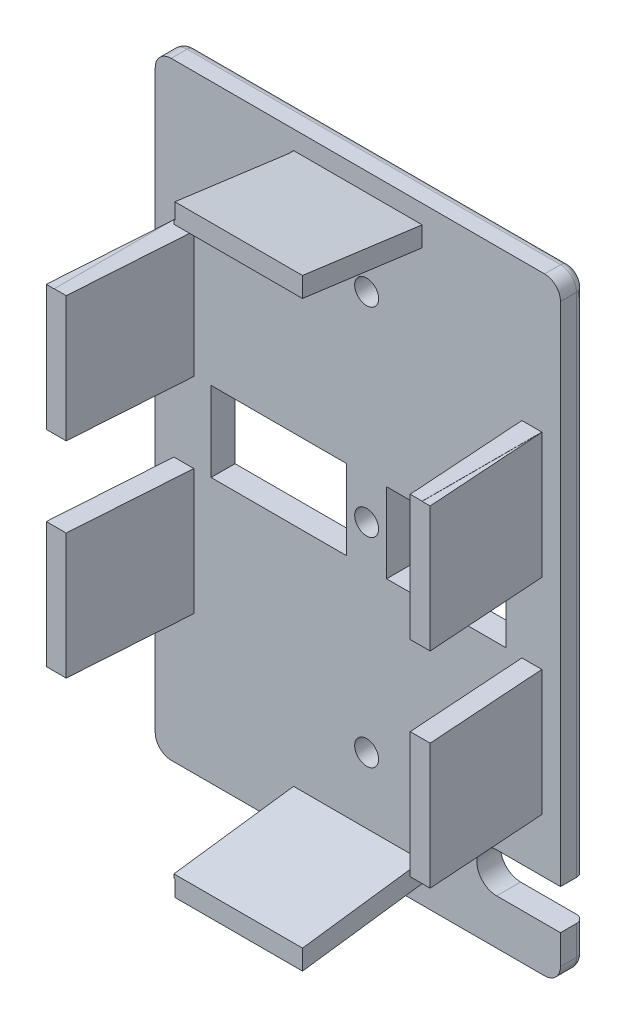
SolidWorks part; units mm, degrees
material "PLA"
ref_plane "Alzado" through (0, 0, 0) normal (0, 0, 1) x (1, 0, 0)
ref_plane "Planta" through (0, 0, 0) normal (0, 1, 0) x (1, 0, 0)
ref_plane "Vista lateral" through (0, 0, 0) normal (1, 0, 0) x (0, 0, -1)
sketch "Croquis1" plane through (0, 0, 0) normal (0, 0, 1) x (1, 0, 0)
  line L1 (25.4, 38.1) -> (-25.4, 38.1)
  line L2 (25.4, 38.1) -> (25.4, -38.1)
  line L3 (25.4, -38.1) -> (-25.4, -38.1)
  line L4 (-25.4, 38.1) -> (-25.4, -38.1)
  line L5 (25.4, 38.1) -> (-25.4, -38.1) construction
  line L6 (25.4, -38.1) -> (-25.4, 38.1) construction
  point P0 (0, 0)
  dimension "D1" = 76.2
  dimension "D2" = 50.8
extrude "Saliente-Extruir1" add sketch "Croquis1" along normal blind 18
sketch "Croquis2" plane through (0, 0, 18) normal (0, 0, 1) x (1, 0, 0)
  line L0 (25.4, 38.1) -> (-25.4, 38.1) construction
  line L1 (-23.06, 35.76) -> (23.06, 35.76)
  line L2 (-23.06, 35.76) -> (-23.06, -35.76)
  line L3 (-23.06, -35.76) -> (23.06, -35.76)
  line L4 (23.06, 35.76) -> (23.06, -35.76)
  line L5 (-25.4, -38.1) -> (25.4, -38.1) construction
  line L6 (-25.4, 38.1) -> (-25.4, -38.1) construction
  line L7 (25.4, -38.1) -> (25.4, 38.1) construction
  line L9 (-25.4, 38.1) -> (25.4, 38.1)
  line L10 (-25.4, 38.1) -> (-25.4, -38.1)
  line L11 (-25.4, -38.1) -> (25.4, -38.1)
  line L12 (25.4, 38.1) -> (25.4, -38.1)
  line L13 (-19.4, 32.1) -> (19.4, 32.1)
  line L14 (-19.4, 32.1) -> (-19.4, -32.1)
  line L15 (-19.4, -32.1) -> (19.4, -32.1)
  line L16 (19.4, 32.1) -> (19.4, -32.1)
  line M9 (-25.4, 38.1) -> (-25.4, -38.1)
  line M10 (-25.4, -38.1) -> (25.4, -38.1)
  line M11 (25.4, -38.1) -> (25.4, 38.1)
  line M12 (25.4, 38.1) -> (-25.4, 38.1)
  dimension "D1" = 2.34
  dimension "D2" = 2.34
  dimension "D3" = 2.34
  dimension "D4" = 2.34
  dimension "D5" = 6
  dimension "D6" = 6
  dimension "D7" = 6
  dimension "D8" = 6
extrude "Cortar-Extruir1" cut sketch "Croquis2" against normal blind 15 contours L1 L4 L3 L2 M12 M9 M10 M11 | L16 L13 L14 L15
sketch "Croquis3" plane through (0, 0, 18) normal (0, 0, 1) x (1, 0, 0)
  line L0 (-23.06, 35.76) -> (-23.06, -35.76) construction
  line L1 (-23.06, 22.1) -> (-19.4, 22.1)
  line L2 (-23.06, 22.1) -> (-23.06, -22.1)
  line L3 (-23.06, -22.1) -> (-19.4, -22.1)
  line L4 (-19.4, 22.1) -> (-19.4, -22.1)
  line L5 (-19.4, 32.1) -> (-19.4, -32.1) construction
  line L6 (-19.4, -32.1) -> (19.4, -32.1) construction
  line L7 (-9.4, -32.1) -> (9.3837, -32.1)
  line L8 (-9.4, -32.1) -> (-9.4, -35.76)
  line L9 (-9.4, -35.76) -> (9.3837, -35.76)
  line L10 (9.3837, -32.1) -> (9.3837, -35.76)
  line L11 (-23.06, -35.76) -> (23.06, -35.76) construction
  line L12 (19.4, 32.1) -> (19.4, -32.1) construction
  line L13 (19.4, -22.1) -> (23.06, -22.1)
  line L14 (19.4, -22.1) -> (19.4, 22.1)
  line L15 (19.4, 22.1) -> (23.06, 22.1)
  line L16 (23.06, -22.1) -> (23.06, 22.1)
  line L17 (23.06, 35.76) -> (23.06, -35.76) construction
  line L18 (-23.06, 35.76) -> (23.06, 35.76) construction
  line L19 (-9.4, 35.76) -> (9.4, 35.76)
  line L20 (-9.4, 35.76) -> (-9.4, 32.1)
  line L21 (-9.4, 32.1) -> (9.4, 32.1)
  line L22 (9.4, 35.76) -> (9.4, 32.1)
  line L23 (-19.4, 32.1) -> (19.4, 32.1) construction
  line L24 (-19.4, 32.1) -> (-19.4, -32.1) construction
  line L25 (19.4, 32.1) -> (19.4, -32.1) construction
  dimension "D1" = 10
  dimension "D2" = 10
  dimension "D3" = 10
  dimension "D4" = 10
  dimension "D5" = 10
  dimension "D6" = 10
  dimension "D7" = 10
extrude "Cortar-Extruir2" [suppressed] cut sketch "Croquis3" against normal blind 7
fillet "Redondeo1" [suppressed] radius 2
fillet "Redondeo2" [suppressed] radius 1
sketch "Croquis5" [suppressed] plane through (0, -38.1, 0) normal (0, -1, 0) x (1, 0, 0)
  line L0 (-23.4, 3) -> (23.4, 3) construction
  line L1 (-3, 3) -> (3, 3)
  line L2 (-3, 3) -> (-3, 1.5)
  line L3 (-3, 1.5) -> (3, 1.5)
  line L4 (3, 3) -> (3, 1.5)
  line L5 (0, 1) -> (0, 3) construction
  line L6 (-23.4, 1) -> (23.4, 1) construction
  dimension "D1" = 3
  dimension "D2" = 3
  dimension "D3" = 1.5
extrude "Cortar-Extruir4" [suppressed] cut sketch "Croquis5" against normal blind 6
sketch "Croquis6" plane through (0, 0, 18) normal (0, 0, 1) x (1, 0, 0)
  line L0 (-23.06, 35.76) -> (-8.06, 35.76)
  line L1 (-23.06, 35.76) -> (23.06, 35.76) construction
  line L2 (-8.06, 35.76) -> (-8.06, 32.1)
  line L3 (-19.4, 32.1) -> (19.4, 32.1) construction
  line L4 (-8.06, 32.1) -> (-19.4, 32.1)
  line L5 (-19.4, 32.1) -> (-19.4, 20.76)
  line L6 (-19.4, 32.1) -> (-19.4, -32.1) construction
  line L7 (-19.4, 20.76) -> (-23.06, 20.76)
  line L8 (-23.06, 35.76) -> (-23.06, -35.76) construction
  line L9 (-23.06, 20.76) -> (-23.06, 35.76)
  line L10 (23.06, 35.76) -> (8.06, 35.76)
  line L11 (-23.06, 35.76) -> (23.06, 35.76) construction
  line L12 (8.06, 35.76) -> (8.06, 32.1)
  line L13 (8.06, 32.1) -> (19.4, 32.1)
  line L14 (19.4, 32.1) -> (19.4, -32.1) construction
  line L15 (19.4, 32.1) -> (19.4, -32.1) construction
  line L16 (19.4, 32.1) -> (19.4, 20.76)
  line L17 (19.4, 20.76) -> (23.06, 20.76)
  line L18 (23.06, 35.76) -> (23.06, -35.76) construction
  line L19 (23.06, 20.76) -> (23.06, 35.76)
  line L20 (-23.06, -35.76) -> (-23.06, -20.76)
  line L21 (-23.06, 35.76) -> (-23.06, -35.76) construction
  line L22 (-23.06, -20.76) -> (-19.4, -20.76)
  line L23 (-19.4, 32.1) -> (-19.4, -32.1) construction
  line L24 (-19.4, -20.76) -> (-19.4, -32.1)
  line L25 (-19.4, -32.1) -> (-8.06, -32.1)
  line L26 (-19.4, -32.1) -> (19.4, -32.1) construction
  line L27 (-8.06, -32.1) -> (-8.06, -35.76)
  line L28 (-23.06, -35.76) -> (23.06, -35.76) construction
  line L29 (-8.06, -35.76) -> (-23.06, -35.76)
  line L30 (23.06, -35.76) -> (8.06, -35.76)
  line L31 (-23.06, -35.76) -> (23.06, -35.76) construction
  line L32 (8.06, -35.76) -> (8.06, -32.1)
  line L33 (-19.4, -32.1) -> (19.4, -32.1) construction
  line L34 (8.06, -32.1) -> (19.4, -32.1)
  line L35 (19.4, -32.1) -> (19.4, -20.76)
  line L36 (19.4, -20.76) -> (23.06, -20.76)
  line L37 (23.06, 35.76) -> (23.06, -35.76) construction
  line L38 (23.06, -20.76) -> (23.06, -35.76)
  dimension "D1" = 15
  dimension "D2" = 15
  dimension "D3" = 15
  dimension "D4" = 15
  dimension "D5" = 15
  dimension "D6" = 15
  dimension "D7" = 15
  dimension "D8" = 15
extrude "Cortar-Extruir8" cut sketch "Croquis6" against normal blind 15
sketch "Croquis10" plane through (0, -20.76, 0) normal (0, -1, 0) x (-1, 0, 0)
  line L0 (23.06, -18) -> (24.06, -18)
  line L1 (24.06, -18) -> (23.06, -3)
  line L2 (23.06, -3) -> (23.06, -18)
  line L3 (-23.06, -18) -> (-24.06, -18)
  line L4 (-24.06, -18) -> (-23.06, -3)
  line L5 (-23.06, -3) -> (-23.06, -18)
  dimension "D1" = 1
  dimension "D2" = 1
extrude "Saliente-Extruir3" add sketch "Croquis10" against normal blind 41.5
sketch "Croquis11" plane through (0, -20.76, 0) normal (0, -1, 0) x (1, 0, 0)
  line L0 (-19.4, 18) -> (-21.56, 18)
  line L1 (-19.4, 18) -> (-24.06, 18) construction
  line L2 (-21.56, 18) -> (-20.56, 3)
  line L3 (-19.4, 3) -> (-23.06, 3) construction
  line L4 (-20.56, 3) -> (-19.4, 3)
  line L5 (-19.4, 18) -> (-19.4, 3)
  dimension "D1" = 2.5
  dimension "D2" = 1.16
extrude "Cortar-Extruir9" cut sketch "Croquis11" against normal blind 51.5
sketch "Croquis12" plane through (0, -20.76, 0) normal (0, -1, 0) x (1, 0, 0)
  line L0 (19.4, 18) -> (19.4, 3)
  line L1 (19.4, 3) -> (20.56, 3)
  line L2 (23.06, 3) -> (19.4, 3) construction
  line L3 (20.56, 3) -> (21.56, 18)
  line L4 (24.06, 18) -> (19.4, 18) construction
  line L5 (21.56, 18) -> (19.4, 18)
  dimension "D1" = 2.5
  dimension "D2" = 1.16
extrude "Cortar-Extruir10" cut sketch "Croquis12" against normal blind 51.5
sketch "Croquis13" plane through (8.06, 0, 0) normal (1, 0, 0) x (0, 0, -1)
  line L0 (-18, -35.76) -> (-18, -37.76)
  line L1 (-18, -37.76) -> (-3, -35.76)
  line L2 (-3, -35.76) -> (-18, -35.76)
  line L3 (-18, 35.76) -> (-18, 37.76)
  line L4 (-18, 37.76) -> (-3, 35.76)
  line L5 (-3, 35.76) -> (-18, 35.76)
  dimension "D1" = 2
  dimension "D2" = 2
extrude "Saliente-Extruir4" add sketch "Croquis13" against normal blind 16
sketch "Croquis14" plane through (8.06, 0, 0) normal (1, 0, 0) x (0, 0, -1)
  line L0 (-3, -32.1) -> (-18, -32.1)
  line L1 (-18, -32.1) -> (-18, -35.26)
  line L2 (-18, -32.1) -> (-18, -37.76) construction
  line L3 (-18, -35.26) -> (-3, -33.26)
  line L4 (-3, -32.1) -> (-3, -35.76) construction
  line L5 (-3, -33.26) -> (-3, -32.1)
  line L6 (-18, 32.1) -> (-18, 35.26)
  line L7 (-18, 37.76) -> (-18, 32.1) construction
  line L8 (-18, 35.26) -> (-3, 33.26)
  line L9 (-3, 35.76) -> (-3, 32.1) construction
  line L10 (-3, 33.26) -> (-3, 32.1)
  line L11 (-3, 32.1) -> (-18, 32.1)
  dimension "D1" = 2.5
  dimension "D2" = 1.16
  dimension "D3" = 2.5
  dimension "D4" = 1.16
extrude "Cortar-Extruir11" cut sketch "Croquis14" against normal blind 16.5
fillet "Redondeo3" radius 2 4 edges at (25.4, 38.1, 1.5) (-25.4, 38.1, 1.5) (-25.4, -38.1, 1.5) (25.4, -38.1, 1.5)
fillet "Redondeo4" radius 1 8 edges at (-24.8142, 37.5142, 0) (-25.4, 0, 0) (-24.8142, -37.5142, 0) (0, -38.1, 0) (24.8142, -37.5142, 0) (25.4, 0, 0) (24.8142, 37.5142, 0) (0, 38.1, 0)
sketch "Croquis15" plane through (0, 0, 18) normal (0, 0, 1) x (1, 0, 0)
  line L0 (-24.06, -0.01) -> (24.06, -0.01) construction
  line L1 (-24.06, 20.74) -> (-24.06, -20.76) construction
  line L2 (24.06, 20.74) -> (24.06, -20.76) construction
  line L4 (-24.06, 4.99) -> (24.06, 4.99)
  line L5 (-24.06, 4.99) -> (-24.06, -5.01)
  line L6 (-24.06, -5.01) -> (24.06, -5.01)
  line L7 (24.06, 4.99) -> (24.06, -5.01)
  dimension "D1" = 5
  dimension "D2" = 5
extrude "Cortar-Extruir12" cut sketch "Croquis15" against normal blind 15
sketch "Croquis16" plane through (0, -38.1, 0) normal (0, -1, 0) x (1, 0, 0)
  line L0 (-23.4, 3) -> (23.4, 3) construction
  line L1 (-4, 3) -> (4, 3)
  line L2 (-4, 3) -> (-4, 1.5)
  line L3 (-4, 1.5) -> (4, 1.5)
  line L4 (4, 3) -> (4, 1.5)
  dimension "D1" = 1.5
  dimension "D2" = 8
  dimension "D3" = 4
extrude "Cortar-Extruir13" cut sketch "Croquis16" against normal blind 2
sketch "Croquis18" plane through (0, 0, 3) normal (0, 0, 1) x (1, 0, 0)
  line L0 (1.1, 38.1) -> (1.1, -38.1) construction
  line L1 (-18.4, 5.1) -> (-1.4, 5.1)
  line L2 (-18.4, 5.1) -> (-18.4, -4.9)
  line L3 (-18.4, -4.9) -> (-1.4, -4.9)
  line L4 (-1.4, 5.1) -> (-1.4, -4.9)
  line L5 (3.6, 5.1) -> (18.6, 5.1)
  line L6 (3.6, 5.1) -> (3.6, -4.9)
  line L7 (3.6, -4.9) -> (18.6, -4.9)
  line L8 (18.6, 5.1) -> (18.6, -4.9)
  line L9 (-25.4, 36.1) -> (-25.4, -36.1) construction
  line L10 (4, -38.1) -> (23.4, -38.1) construction
  line L43 (23.4, 38.1) -> (-23.4, 38.1) construction
  line L46 (-25.4, 0) -> (25.4, 0) construction
  line L47 (25.4, -36.1) -> (25.4, 36.1) construction
  circle A0 centre (1.1, 0) radius 1.5
  circle A1 centre (1.1, 25) radius 1.5
  circle A2 centre (1.1, -25) radius 1.5
  dimension "D9" = 3
  dimension "D10" = 3
  dimension "D11" = 3
  dimension "D1" = 17
  dimension "D2" = 10
  dimension "D3" = 15
  dimension "D4" = 10
  dimension "D5" = 5
  dimension "D6" = 7
  dimension "D7" = 26.5
  dimension "D8" = 33
  dimension "D12" = 25
  dimension "D13" = 25
  dimension "D14" = 33
extrude "Cortar-Extruir15" cut sketch "Croquis18" against normal blind 3
sketch "Croquis19" plane through (0, 0, 3) normal (0, 0, 1) x (1, 0, 0)
  line L0 (25.4, -29.9199) -> (17.4, -29.9199) construction
  line L1 (25.4, -36.1) -> (25.4, 36.1) construction
  line L2 (25.4, -32.4199) -> (17.4, -32.4199)
  line L3 (25.4, -27.4199) -> (17.4, -27.4199)
  arc A0 (25.4, -32.4199) -> (25.4, -27.4199) centre (25.4, -29.9199) ccw
  arc A1 (17.4, -27.4199) -> (17.4, -32.4199) centre (17.4, -29.9199) ccw
  point P4 (21.4, -29.9199)
  point P9 (21.4, -32.4199)
  dimension "D1" = 8
  dimension "D2" = 5
extrude "Cortar-Extruir16" cut sketch "Croquis19" against normal blind 10
